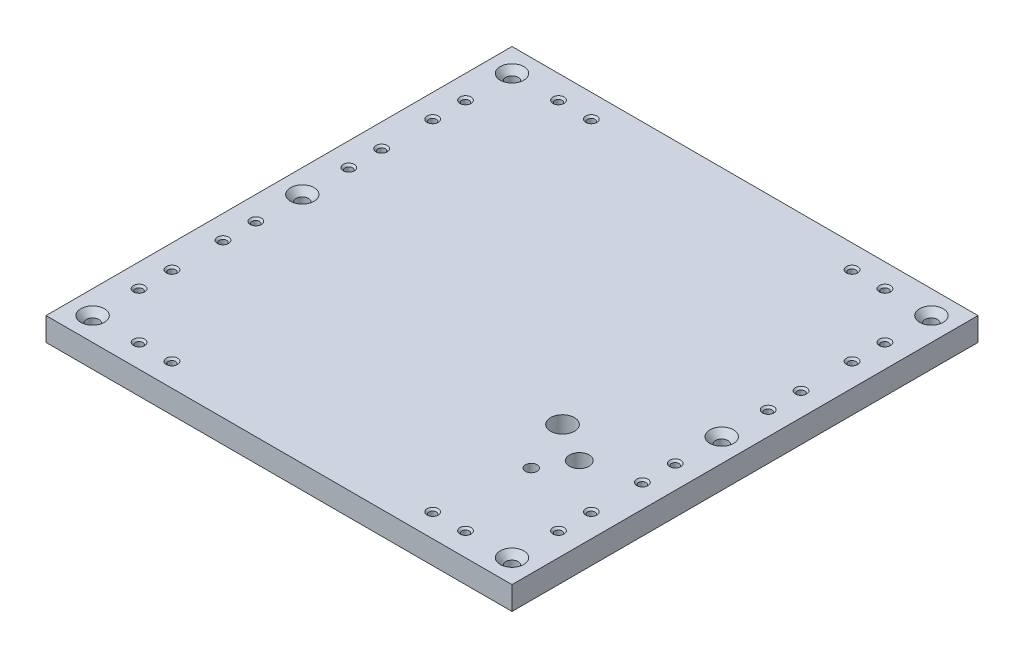
SolidWorks part; units mm, degrees
material "6061 Alloy"
ref_plane "Front Plane" through (0, 0, 0) normal (0, 0, 1) x (1, 0, 0)
ref_plane "Top Plane" through (0, 0, 0) normal (0, 1, 0) x (1, 0, 0)
ref_plane "Right Plane" through (0, 0, 0) normal (1, 0, 0) x (0, 0, -1)
sketch "Sketch1" plane through (0, 0, 0) normal (0, 1, 0) x (1, 0, 0)
  line L1 (-127, -127) -> (127, -127)
  line L2 (-127, -127) -> (-127, 127)
  line L3 (-127, 127) -> (127, 127)
  line L4 (127, -127) -> (127, 127)
  line L5 (-127, -127) -> (127, 127) construction
  line L6 (-127, 127) -> (127, -127) construction
  point P4 (0, 0)
  dimension "D1" = 254
  dimension "D2" = 254
extrude "Boss-Extrude1" add sketch "Sketch1" along normal blind 12.7
sketch "Sketch2" plane through (0, 12.7, 0) normal (0, 1, 0) x (1, 0, 0)
  line L0 (-127, -127) -> (127, -127) construction
  line L1 (-101.6, -127) -> (101.6, -127)
  line L2 (-101.6, -127) -> (-101.6, -12.7)
  line L3 (-101.6, -12.7) -> (101.6, -12.7)
  line L4 (101.6, -127) -> (101.6, -12.7)
  line L5 (-101.6, -127) -> (101.6, -12.7) construction
  line L6 (-101.6, -12.7) -> (101.6, -127) construction
  line L7 (127, 127) -> (-127, 127) construction
  line L8 (101.6, 127) -> (-101.6, 127)
  line L9 (101.6, 127) -> (101.6, 12.7)
  line L10 (101.6, 12.7) -> (-101.6, 12.7)
  line L11 (-101.6, 127) -> (-101.6, 12.7)
  line L12 (101.6, 127) -> (-101.6, 12.7) construction
  line L13 (101.6, 12.7) -> (-101.6, 127) construction
  line L14 (-127, 127) -> (-127, -127) construction
  line L15 (127, -127) -> (127, 127) construction
  point P4 (0, -69.85)
  point P11 (0, 69.85)
  dimension "D1" = 25.4
  dimension "D2" = 25.4
  dimension "D3" = 25.4
extrude "Cut-Extrude1" cut sketch "Sketch2" against normal through all
sketch "Sketch3" plane through (0, 12.7, 0) normal (0, 1, 0) x (1, 0, 0)
  line L0 (-114.3, -43.2435) -> (-114.3, -127) construction
  line L1 (-127, -127) -> (-101.6, -127) construction
  line L2 (-114.3, -43.2435) -> (-114.3, -25.3365) construction
  line L3 (-127, 0) -> (127, 0) construction
  line L4 (-127, 127) -> (-127, -127) construction
  line L5 (127, -127) -> (127, 127) construction
  line L6 (0, 12.7) -> (0, -12.7)
  line L7 (-101.6, 12.7) -> (101.6, 12.7) construction
  line L8 (101.6, -12.7) -> (-101.6, -12.7) construction
  line L9 (-114.3, 127) -> (-114.3, -127)
  line L10 (-101.6, 127) -> (-127, 127) construction
  line L11 (-114.3, 114.3) -> (114.3, 114.3)
  circle A0 centre (-114.3, -25.3365) radius 2.0193
  circle A1 centre (-114.3, -43.2435) radius 2.0193
  circle A2 centre (-114.3, 43.2435) radius 2.0193
  circle A3 centre (-114.3, 25.3365) radius 2.0193
  circle A4 centre (-114.3, -88.9635) radius 2.0193
  circle A5 centre (-114.3, -71.0565) radius 2.0193
  circle A6 centre (-114.3, 71.0565) radius 2.0193
  circle A7 centre (-114.3, 88.9635) radius 2.0193
  circle A8 centre (114.3, -88.9635) radius 2.0193
  circle A9 centre (114.3, -71.0565) radius 2.0193
  circle A10 centre (114.3, -43.2435) radius 2.0193
  circle A11 centre (114.3, -25.3365) radius 2.0193
  circle A12 centre (114.3, 25.3365) radius 2.0193
  circle A13 centre (114.3, 43.2435) radius 2.0193
  circle A14 centre (114.3, 71.0565) radius 2.0193
  circle A15 centre (114.3, 88.9635) radius 2.0193
  point P17 (-114.3, 0)
  point P29 (-114.3, -114.3)
  point P36 (-114.3, 114.3)
  point P37 (114.3, -114.3)
  point P46 (114.3, 0)
  point P55 (114.3, 114.3)
  point P58 (-88.9635, 114.3)
  point P59 (-71.0565, 114.3)
  point P60 (71.0565, 114.3)
  point P61 (88.9635, 114.3)
  point P62 (88.9635, -114.3)
  point P63 (71.0565, -114.3)
  point P64 (-71.0565, -114.3)
  point P65 (-88.9635, -114.3)
  dimension "D3" = 4.0386
  dimension "D5" = 4.0386
  dimension "D8" = 4.0386
  dimension "D1" = 83.7565
  dimension "D2" = 17.907
  dimension "D4" = 12.7
  dimension "D6" = 12.7
  dimension "D7" = 25.3365
  dimension "D9" = 17.907
  dimension "D10" = 25.3365
  dimension "D11" = 17.907
  dimension "D12" = 17.907
  dimension "D13" = 25.3365
sketch "Sketch8" plane through (0, 12.7, 0) normal (0, 1, 0) x (1, 0, 0)
  circle A0 centre (39.9999, 0) radius 2.8378
  point P0 (0, 0)
  dimension "D1" = 39.9999
extrude "Cut-Extrude4" [suppressed] cut sketch "Sketch8" against normal through all
sketch "Sketch9" [suppressed] plane through (0, 12.7, 0) normal (0, 1, 0) x (1, 0, 0)
  line L0 (34.9199, -9.525) -> (34.9199, -12.7) construction
  line L1 (34.9199, 9.525) -> (50.7949, 9.525)
  line L2 (34.9199, 9.525) -> (34.9199, -9.525)
  line L3 (34.9199, -9.525) -> (50.7949, -9.525)
  line L4 (50.7949, 9.525) -> (50.7949, -9.525)
  line L5 (34.9199, 9.525) -> (50.7949, -9.525) construction
  line L6 (34.9199, -9.525) -> (50.7949, 9.525) construction
  line L7 (101.6, -12.7) -> (-101.6, -12.7) construction
  line L8 (34.9199, 9.525) -> (34.9199, 12.7) construction
  line L9 (-101.6, 12.7) -> (101.6, 12.7) construction
  circle A0 centre (39.9999, 0) radius 2.8378 construction
  point P4 (42.8574, 0)
  dimension "D2" = 5.08
  dimension "D1" = 15.875
  dimension "D3" = 19.05
extrude "Cut-Extrude5" [suppressed] cut sketch "Sketch9" against normal blind 1.5875
sketch "Sketch10" [suppressed] plane through (0, 12.7, 0) normal (0, 1, 0) x (1, 0, 0)
  circle A0 centre (34.9199, 9.525) radius 1.5875
  circle A1 centre (34.9199, -9.525) radius 1.5875
  circle A2 centre (50.7949, -9.525) radius 1.5875
  circle A3 centre (50.7949, 9.525) radius 1.5875
  dimension "D1" = 3.175
extrude "Cut-Extrude6" [suppressed] cut sketch "Sketch10" against normal up to surface (1.5875 mm away)
sketch "Sketch11" plane through (0, 12.7, 0) normal (0, 1, 0) x (1, 0, 0)
  line L1 (-101.6, 127) -> (101.6, 127)
  line L2 (-101.6, 127) -> (-101.6, 12.7)
  line L3 (-101.6, 12.7) -> (101.6, 12.7)
  line L4 (101.6, 127) -> (101.6, 12.7)
  line L5 (-101.6, 127) -> (101.6, 12.7) construction
  line L6 (-101.6, 12.7) -> (101.6, 127) construction
  line L7 (101.6, -12.7) -> (-101.6, -12.7)
  line L8 (101.6, -12.7) -> (101.6, -127)
  line L9 (101.6, -127) -> (-101.6, -127)
  line L10 (-101.6, -12.7) -> (-101.6, -127)
  line L11 (101.6, -12.7) -> (-101.6, -127) construction
  line L12 (101.6, -127) -> (-101.6, -12.7) construction
  point P4 (0, 69.85)
  point P11 (0, -69.85)
extrude "Boss-Extrude2" add sketch "Sketch11" against normal up to surface (12.7 mm away) up to face at (0, 0, 0)
sketch "Sketch12" plane through (0, 12.7, 0) normal (0, 1, 0) x (1, 0, 0)
  line L0 (0, 0) -> (12.7, 0) construction
  line L1 (0, 0) -> (-12.7, 0) construction
  circle A0 centre (12.7, 0) radius 1.1303
  circle A1 centre (-12.7, 0) radius 1.1303
  dimension "D1" = 2.2606
  dimension "D2" = 12.7
extrude "Cut-Extrude7" [suppressed] cut sketch "Sketch12" against normal through all
sketch "Sketch13" plane through (0, 12.7, 0) normal (0, 1, 0) x (1, 0, 0)
  line L0 (0, 0) -> (86.819, -50.125) construction
  line L1 (0, 0) -> (127, 0) construction
  line L2 (127, -127) -> (127, 127) construction
  circle A0 centre (86.819, -50.125) radius 5.3578
  circle A1 centre (65.1684, -37.625) radius 6.4897
  point P0 (0, 0)
  point P1 (65.1684, -37.625)
  point P3 (86.819, -50.125)
  dimension "D4" = 10.7156
  dimension "D5" = 12.9794
  dimension "D1" = 75.25
  dimension "D2" = 25
  dimension "D3" = 30
extrude "Cut-Extrude8" cut sketch "Sketch13" against normal through all
sketch "Sketch14" plane through (0, 12.7, 0) normal (0, 1, 0) x (1, 0, 0)
  line L0 (65.1684, -37.625) -> (86.819, -50.125) construction
  line L1 (86.819, -50.125) -> (78.819, -63.9814) construction
  line L2 (78.819, -63.9814) -> (77.2379, -66.72) construction
  circle A0 centre (77.2379, -66.72) radius 3.1623
  dimension "D2" = 6.3246
  dimension "D1" = 16
extrude "Cut-Extrude9" cut sketch "Sketch14" against normal through all
hole_wizard "#10-32 Tapped Hole2" positions "Sketch17" profile "Sketch18" tap size "#10-32" standard "ANSI Inch" end condition through all
sketch "Sketch17" plane through (0, 12.7, 0) normal (0, 1, 0) x (1, 0, 0)
  line L0 (-127, -127) -> (127, -127) construction
  line L1 (-127, 127) -> (-127, -127) construction
  point P0 (-114.3, -25.3365)
  point P3 (-114.3, -43.2435)
  point P6 (-114.3, -71.0565)
  point P8 (-114.3, -88.9635)
  point P13 (-88.9635, -114.3)
  point P15 (-71.0565, -114.3)
  dimension "D1" = 38.0365
  dimension "D2" = 17.907
  dimension "D3" = 38.0365
  dimension "D4" = 17.907
  dimension "D5" = 12.7
  dimension "D6" = 12.7
sketch "Sketch18" plane through (-114.3, 12.7, 25.3365) normal (1, 0, 0) x (0, 0, 1)
  line L0 (0, 0) -> (0, 12.7)
  line L1 (0, 12.7) -> (2.0193, 12.7)
  line L2 (2.0193, 12.7) -> (2.0193, 1.0287)
  line L3 (2.0193, 1.0287) -> (3.048, 0)
  line L5 (3.048, 0) -> (0, 0)
  line L6 (-2.0193, 1.0287) -> (-3.048, 0) construction
  line L11 (0, -6.35) -> (0, 107.95) construction
  dimension "Thru Tap Drill Dia." = 4.0386
  dimension "Thru Tap Drill Depth" = 12.7
  dimension "Near C'Sink Dia." = 6.096
  dimension "Near C'Sink Angle" = 90
cosmetic thread "Hole Thread3"
cosmetic thread "Hole Thread4"
cosmetic thread "Hole Thread5"
cosmetic thread "Hole Thread6"
cosmetic thread "Hole Thread7"
cosmetic thread "Hole Thread8"
mirror "Mirror1" about plane through (0, 0, 0) normal (0, 0, 1) of "#10-32 Tapped Hole2"
mirror "Mirror2" about plane through (0, 0, 0) normal (1, 0, 0) of "#10-32 Tapped Hole2", "Mirror1"
sketch "Sketch19" plane through (0, 12.7, 0) normal (0, 1, 0) x (1, 0, 0)
  line L0 (-114.3, 25.3365) -> (-114.3, 0) construction
  line L1 (-114.3, 0) -> (-114.3, -25.3365) construction
  line L2 (-127, -127) -> (127, -127) construction
  line L4 (127, 127) -> (-127, 127) construction
  point P7 (-114.3, -107.95)
  point P10 (-114.3, 107.95)
  dimension "D1" = 19.05
  dimension "D3" = 19.05
hole_wizard "CSK for 1/4 Flat Head Machine Screw1" positions "Sketch20" profile "Sketch21" countersink size "1/4" standard "ANSI Inch" end condition through all
sketch "Sketch20" plane through (0, 12.7, 0) normal (0, 1, 0) x (1, 0, 0)
  line L0 (127, 127) -> (-127, 127) construction
  line L1 (-127, -127) -> (127, -127) construction
  point P0 (-114.3, 0)
  point P3 (-114.3, 114.3)
  point P5 (-114.3, -114.3)
  dimension "D1" = 12.7
  dimension "D2" = 12.7
sketch "Sketch21" plane through (-114.3, 12.7, 0) normal (1, 0, 0) x (0, 0, 1)
  line L0 (0, 0) -> (0, 12.7)
  line L1 (0, 12.7) -> (3.3782, 12.7)
  line L2 (3.3782, 12.7) -> (3.3782, 3.5209)
  line L3 (3.3782, 3.5209) -> (6.4389, 0)
  line L5 (6.4389, 0) -> (0, 0)
  line L6 (-3.3782, 3.5209) -> (-6.4389, 0) construction
  line L11 (0, -6.35) -> (0, 107.95) construction
  dimension "Thru Hole Dia." = 6.7564
  dimension "Thru Hole Depth" = 12.7
  dimension "Near C'Sink Dia." = 12.8778
  dimension "Near C'Sink Angle" = 82
mirror "Mirror3" about plane through (0, 0, 0) normal (1, 0, 0) of "CSK for 1/4 Flat Head Machine Screw1"
sketch3d "Sketch_MAC1-1_ONEPIECE_BASE_MILLING_1" [suppressed]
  line L0 (-127, 12.7, 76.2) -> (-117, 12.7, 76.2)
  line L1 (-127, 12.7, 76.2) -> (-127, 12.7, 66.2)
  point P0 (-127, 12.7, 76.2)
  point P1 (-117, 12.7, 76.2)
  point P2 (-127, 12.7, 66.2)
equation "\"A\"=3.03281"
equation "\"wing_spar_height\"= 2"
equation "\"wing_spar_thickness\"= .5"
equation "\"frame_width\"= 10"
equation "\"load_length\"= 130mm"
equation "\"load_width\"= 32mm"
equation "\"load_hole_space\"= 75.25mm"
equation "\"D1@Sketch13\"=\"load_hole_space\""
equation "\"load_hole_space_2\"= 25mm"
equation "\"D2@Sketch13\"=\"load_hole_space_2\""
equation "\"D1@Sketch14\"=\"load_width\"/2"
